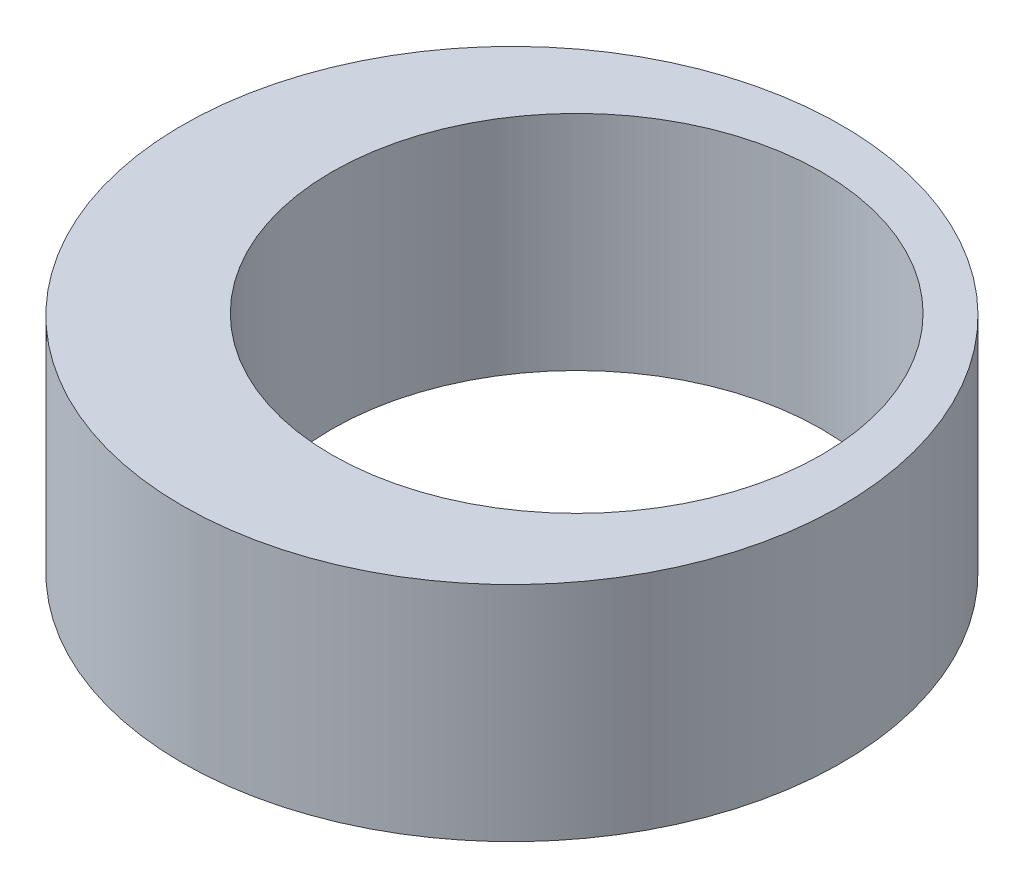
SolidWorks part; units mm, degrees
ref_plane "Front Plane" through (0, 0, 0) normal (0, 0, 1) x (1, 0, 0)
ref_plane "Top Plane" through (0, 0, 0) normal (0, 1, 0) x (1, 0, 0)
ref_plane "Right Plane" through (0, 0, 0) normal (1, 0, 0) x (0, 0, -1)
sketch "Sketch1" plane through (0, 0, 0) normal (0, 1, 0) x (1, 0, 0)
  circle A0 centre (0, 0) radius 7.4
  dimension "D1" = 14.8
extrude "Boss-Extrude1" add sketch "Sketch1" along normal blind 5
sketch "Sketch2" plane through (0, 5, 0) normal (0, 1, 0) x (1, 0, 0)
  circle A1 centre (0.6864, 0.7677) radius 5.5
  dimension "D1" = 11
extrude "Cut-Extrude1" cut sketch "Sketch2" against normal blind 5
